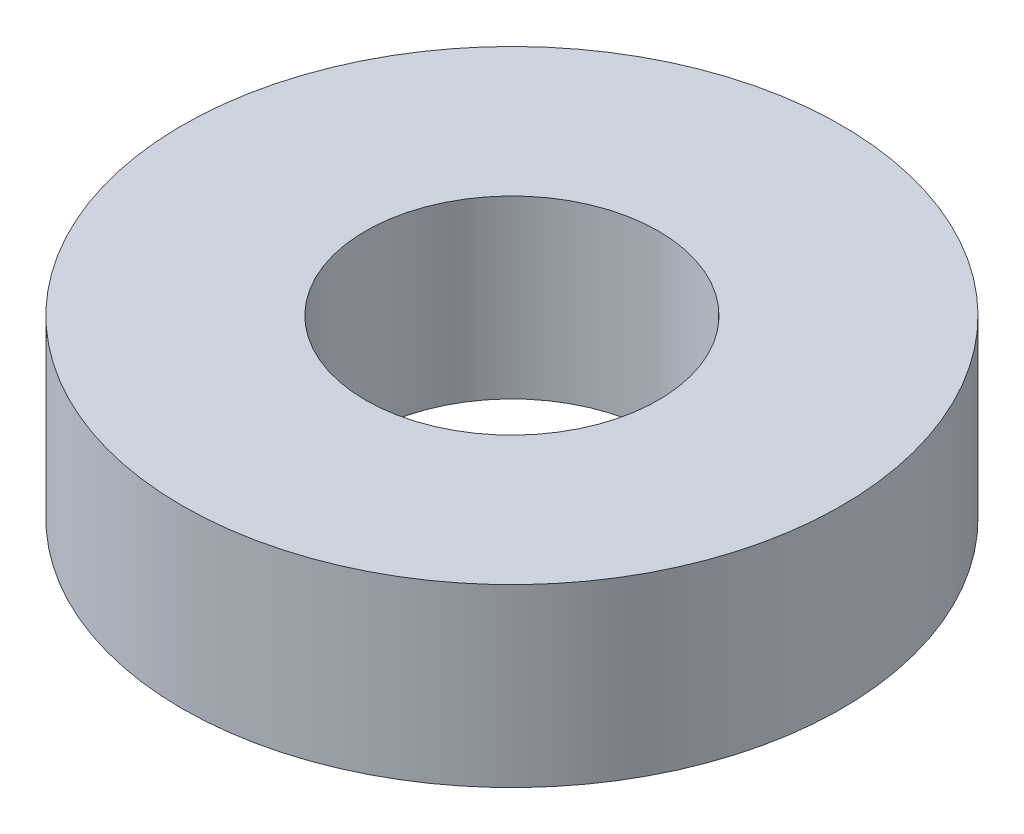
SolidWorks part; units mm, degrees
ref_plane "Front Plane" through (0, 0, 0) normal (0, 0, 1) x (1, 0, 0)
ref_plane "Top Plane" through (0, 0, 0) normal (0, 1, 0) x (1, 0, 0)
ref_plane "Right Plane" through (0, 0, 0) normal (1, 0, 0) x (0, 0, -1)
sketch "Sketch1" plane through (0, 0, 0) normal (0, 1, 0) x (1, 0, 0)
  circle A0 centre (0, 0) radius 10
  circle A1 centre (0, 0) radius 22.5
  dimension "D1" = 20
  dimension "D2" = 45
extrude "Boss-Extrude1" add sketch "Sketch1" along normal blind 12
